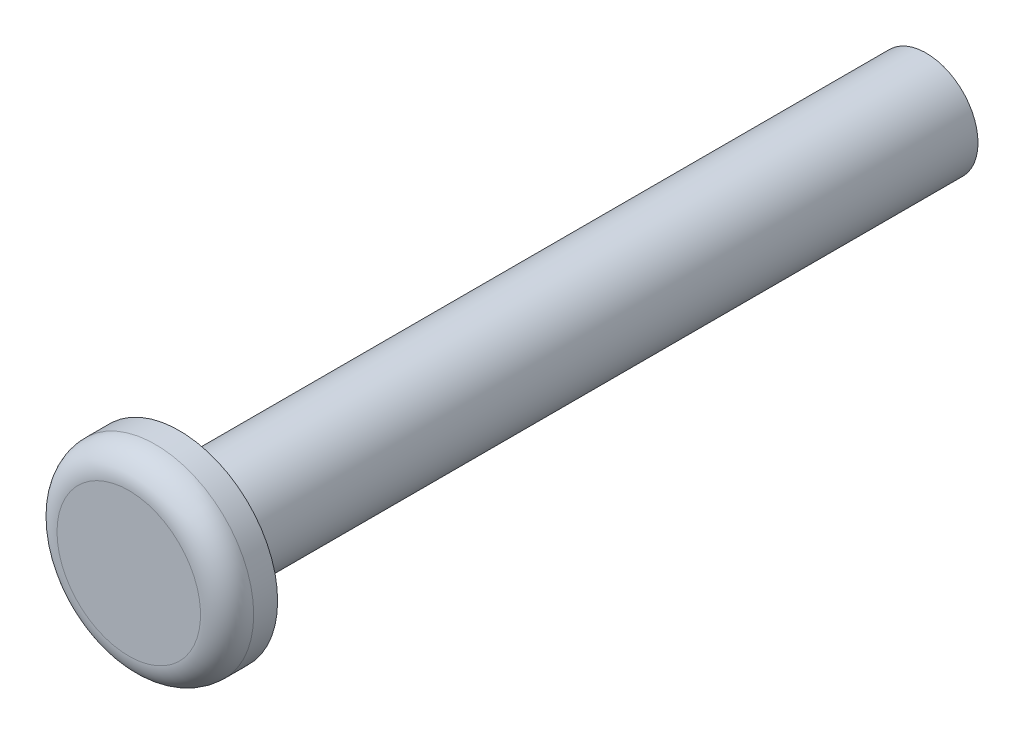
SolidWorks part; units mm, degrees
ref_plane "Front Plane" through (0, 0, 0) normal (0, 0, 1) x (1, 0, 0)
ref_plane "Top Plane" through (0, 0, 0) normal (0, 1, 0) x (1, 0, 0)
ref_plane "Right Plane" through (0, 0, 0) normal (1, 0, 0) x (0, 0, -1)
sketch "Sketch1" plane through (0, 0, 0) normal (1, 0, 0) x (0, 0, -1)
  line L0 (1.9, 1.95) -> (1.9, 3.7)
  line L1 (0, 0) -> (30, 0)
  line L3 (1.9, 1.95) -> (30, 1.95)
  line L4 (30, 0) -> (30, 1.95)
  line L5 (1.9, 3.7) -> (0, 3.7)
  line L6 (0, 3.7) -> (0, 0)
  dimension "D1" = 30
  dimension "D2" = 1.95
  dimension "D3" = 3.7
  dimension "D4" = 1.9
revolve "Revolve1" add sketch "Sketch1" angle 360 about L1
fillet "Fillet1" radius 1 1 edges at (3.7, 0, 0)
